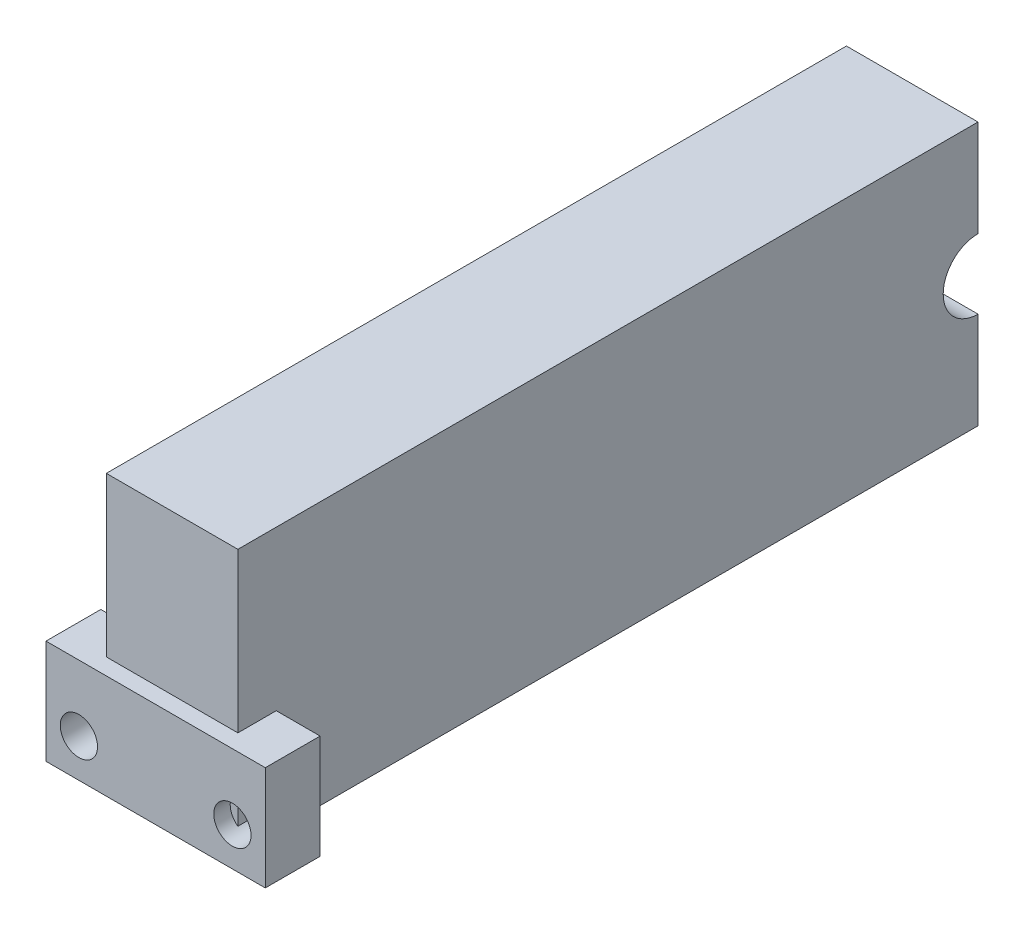
SolidWorks part; units mm, degrees
material "7075-T6 (SN)"
ref_plane "Front Plane" through (0, 0, 0) normal (0, 0, 1) x (1, 0, 0)
ref_plane "Top Plane" through (0, 0, 0) normal (0, 1, 0) x (1, 0, 0)
ref_plane "Right Plane" through (0, 0, 0) normal (1, 0, 0) x (0, 0, -1)
sketch "Sketch1" plane through (0, 0, 0) normal (0, 0, 1) x (1, 0, 0)
  line L1 (-30, 24.5) -> (-10, 24.5)
  line L2 (-30, 24.5) -> (-30, 34)
  line L3 (-30, 34) -> (-10, 34)
  line L4 (-10, 24.5) -> (-10, 34)
  circle A0 centre (-27, 28) radius 1.7
  circle A1 centre (-13, 28) radius 1.7
extrude "Five_mm_Attachment_Foot" add sketch "Sketch1" along normal blind 5 from offset 5
sketch "Sketch2" plane through (0, 0, 0) normal (0, 0, 1) x (1, 0, 0)
  line L1 (-26, 24.5) -> (-14, 24.5)
  line L2 (-26, 24.5) -> (-26, 48.5)
  line L3 (-26, 48.5) -> (-14, 48.5)
  line L4 (-14, 24.5) -> (-14, 48.5)
extrude "Deep_Actuator_Web" add sketch "Sketch2" along normal blind 67.5 from offset 69
sketch "Sketch3" plane through (0, 0, 0) normal (1, 0, 0) x (0, 0, -1)
  circle A0 centre (69, 36.5) radius 3.175
extrude "Quarter20_Axial_Thread_Major_Envelope" cut sketch "Sketch3" against normal through all and the other way through all
